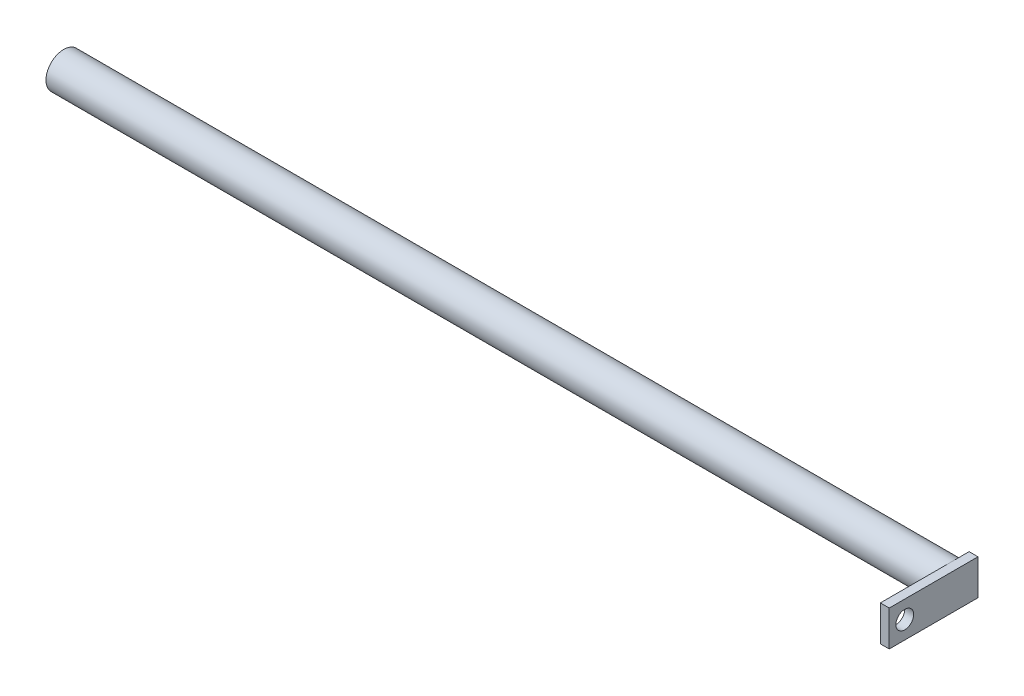
SolidWorks part; units mm, degrees
ref_plane "Front Plane" through (0, 0, 0) normal (1, 0, 0) x (0, 1, 0)
ref_plane "Top Plane" through (0, 0, 0) normal (0, 0, 1) x (0, 1, 0)
ref_plane "Right Plane" through (0, 0, 0) normal (0, 1, 0) x (-1, 0, 0)
sketch "Sketch2" plane through (0, 0, 0) normal (0, 1, 0) x (-1, 0, 0)
  line L1 (-200, 0) -> (200, 0)
  line L2 (-200, 0) -> (-200, -8)
  line L3 (-200, -8) -> (200, -8)
  line L4 (200, 0) -> (200, -8)
  point P4 (0, 0)
  dimension "D1" = 400
  dimension "D2" = 8
revolve "Revolve1" add sketch "Sketch2" angle 360 about L1
sketch "Sketch3" plane through (200, 0, 0) normal (1, 0, 0) x (0, 1, 0)
  line L1 (-8, -8) -> (8, -8)
  line L2 (-8, -8) -> (-8, 32)
  line L3 (-8, 32) -> (8, 32)
  line L4 (8, -8) -> (8, 32)
  circle A0 centre (0, 0) radius 8 construction
  point P6 (0, -8)
  dimension "D1" = 40
extrude "Boss-Extrude1" add sketch "Sketch3" along normal blind 4
sketch "Sketch5" plane through (200, 0, 0) normal (-1, 0, 0) x (0, -1, 0)
  circle A0 centre (0, 25) radius 4
  dimension "D1" = 8
  dimension "D2" = 25
extrude "Cut-Extrude1" cut sketch "Sketch5" against normal up to surface (4 mm away) up to face at (204, 0, 12)
